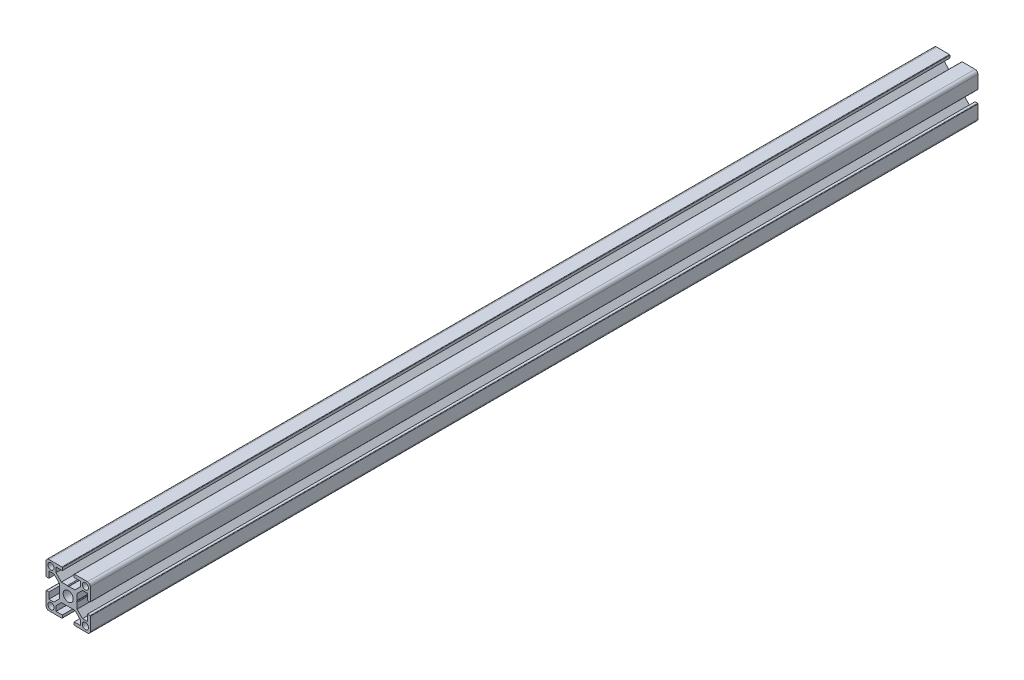
SolidWorks part; units mm, degrees
ref_plane "Front Plane" through (0, 0, 0) normal (0, 0, 1) x (1, 0, 0)
ref_plane "Top Plane" through (0, 0, 0) normal (0, 1, 0) x (1, 0, 0)
ref_plane "Right Plane" through (0, 0, 0) normal (1, 0, 0) x (0, 0, -1)
ref_plane "Plane1" through (0, 0, 0) normal (0, 0, 1) x (1, 0, 0)
sketch "Sketch1" plane through (0, 0, 0) normal (0, 0, 1) x (1, 0, 0)
  line L0 (-15, -4.3) -> (-15, -13)
  line L1 (-13, -15) -> (-4.3, -15)
  line L2 (-4, -14.7) -> (-4, -13)
  line L3 (-4, -13) -> (-8.25, -13)
  line L4 (-8.25, -13) -> (-8.25, -9.6642)
  line L5 (-8.25, -9.6642) -> (-4.5858, -6)
  line L6 (-4.5858, -6) -> (-0.5196, -6)
  line L7 (-0.5196, -6) -> (0, -5.7)
  line L8 (0, -5.7) -> (0.5196, -6)
  line L9 (0.5196, -6) -> (4.5858, -6)
  line L10 (4.5858, -6) -> (8.25, -9.6642)
  line L11 (8.25, -9.6642) -> (8.25, -13)
  line L12 (8.25, -13) -> (4, -13)
  line L13 (4, -13) -> (4, -14.7)
  line L14 (4.3, -15) -> (13, -15)
  line L15 (15, -13) -> (15, -4.3)
  line L16 (14.7, -4) -> (13, -4)
  line L17 (13, -4) -> (13, -8.25)
  line L18 (13, -8.25) -> (9.6642, -8.25)
  line L19 (9.6642, -8.25) -> (6, -4.5858)
  line L20 (6, -4.5858) -> (6, -0.5196)
  line L21 (6, -0.5196) -> (5.7, 0)
  line L22 (5.7, 0) -> (6, 0.5196)
  line L23 (6, 0.5196) -> (6, 4.5858)
  line L24 (6, 4.5858) -> (9.6642, 8.25)
  line L25 (9.6642, 8.25) -> (13, 8.25)
  line L26 (13, 8.25) -> (13, 4)
  line L27 (13, 4) -> (14.7, 4)
  line L28 (15, 4.3) -> (15, 13)
  line L29 (13, 15) -> (4.3, 15)
  line L30 (4, 14.7) -> (4, 13)
  line L31 (4, 13) -> (8.25, 13)
  line L32 (8.25, 13) -> (8.25, 9.6642)
  line L33 (8.25, 9.6642) -> (4.5858, 6)
  line L34 (4.5858, 6) -> (0.5196, 6)
  line L35 (0.5196, 6) -> (0, 5.7)
  line L36 (0, 5.7) -> (-0.5196, 6)
  line L37 (-0.5196, 6) -> (-4.5858, 6)
  line L38 (-4.5858, 6) -> (-8.25, 9.6642)
  line L39 (-8.25, 9.6642) -> (-8.25, 13)
  line L40 (-8.25, 13) -> (-4, 13)
  line L41 (-4, 13) -> (-4, 14.7)
  line L42 (-4.3, 15) -> (-13, 15)
  line L43 (-15, 13) -> (-15, 4.3)
  line L44 (-14.7, 4) -> (-13, 4)
  line L45 (-13, 4) -> (-13, 8.25)
  line L46 (-13, 8.25) -> (-9.6642, 8.25)
  line L47 (-9.6642, 8.25) -> (-6, 4.5858)
  line L48 (-6, 4.5858) -> (-6, 0.5196)
  line L49 (-6, 0.5196) -> (-5.7, 0)
  line L50 (-5.7, 0) -> (-6, -0.5196)
  line L51 (-6, -0.5196) -> (-6, -4.5858)
  line L52 (-6, -4.5858) -> (-9.6642, -8.25)
  line L53 (-9.6642, -8.25) -> (-13, -8.25)
  line L54 (-13, -8.25) -> (-13, -4)
  line L55 (-13, -4) -> (-14.7, -4)
  arc A0 (-15, -13) -> (-13, -15) centre (-13, -13) ccw
  arc A1 (-4.3, -15) -> (-4, -14.7) centre (-4.3, -14.7) ccw
  arc A2 (4, -14.7) -> (4.3, -15) centre (4.3, -14.7) ccw
  arc A3 (13, -15) -> (15, -13) centre (13, -13) ccw
  arc A4 (15, -4.3) -> (14.7, -4) centre (14.7, -4.3) ccw
  arc A5 (14.7, 4) -> (15, 4.3) centre (14.7, 4.3) ccw
  arc A6 (15, 13) -> (13, 15) centre (13, 13) ccw
  arc A7 (4.3, 15) -> (4, 14.7) centre (4.3, 14.7) ccw
  arc A8 (-4, 14.7) -> (-4.3, 15) centre (-4.3, 14.7) ccw
  arc A9 (-13, 15) -> (-15, 13) centre (-13, 13) ccw
  arc A10 (-15, 4.3) -> (-14.7, 4) centre (-14.7, 4.3) ccw
  arc A11 (-14.7, -4) -> (-15, -4.3) centre (-14.7, -4.3) ccw
  circle A12 centre (11.625, -11.625) radius 2.1
  circle A13 centre (11.625, 11.625) radius 2.1
  circle A14 centre (0, 0) radius 3.4
  circle A15 centre (-11.625, -11.625) radius 2.1
  circle A16 centre (-11.625, 11.625) radius 2.1
extrude "Boss-Extrude1" add sketch "Sketch1" against normal blind 600
